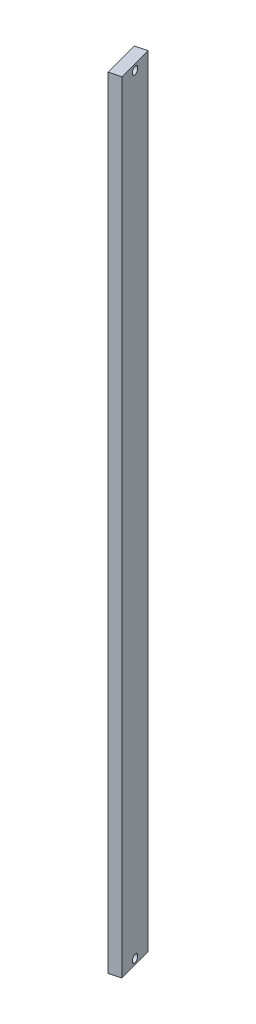
SolidWorks part; units mm, degrees
ref_plane "Front Plane" through (0, 0, 0) normal (0, 0, 1) x (1, 0, 0)
ref_plane "Top Plane" through (0, 0, 0) normal (0, 1, 0) x (1, 0, 0)
ref_plane "Right Plane" through (0, 0, 0) normal (1, 0, 0) x (0, 0, -1)
sketch "Sketch1" plane through (0, 0, 0) normal (0, 1, 0) x (1, 0, 0)
  line L0 (0, 0) -> (0, 39.444) construction
  line L1 (0, 39.444) -> (-19.722, 34.1595)
  line L2 (-19.722, 34.1595) -> (-34.1595, 19.722)
  line L3 (-34.1595, 19.722) -> (-39.444, 0)
  line L4 (-39.444, 0) -> (-34.1595, -19.722)
  line L5 (-34.1595, -19.722) -> (-19.722, -34.1595)
  line L6 (-19.722, -34.1595) -> (0, -39.444)
  line L7 (0, -39.444) -> (19.722, -34.1595)
  line L8 (19.722, -34.1595) -> (34.1595, -19.722)
  line L9 (34.1595, -19.722) -> (39.444, 0)
  line L10 (39.444, 0) -> (34.1595, 19.722)
  line L11 (34.1595, 19.722) -> (19.722, 34.1595)
  line L12 (19.722, 34.1595) -> (0, 39.444)
  line L13 (39.444, 0) -> (34.1595, 19.722)
  line L14 (39.444, 0) -> (45.5777, 1.6435)
  line L15 (34.1595, 19.722) -> (40.2932, 21.3655)
  line L16 (45.5777, 1.6435) -> (40.2932, 21.3655)
  circle A0 centre (0, 0) radius 38.1 construction
  dimension "D1" = 76.2
  dimension "D2" = 6.35
extrude "Boss-Extrude1" add sketch "Sketch1" along normal blind 431.8 contours L14 L16 L15 L10
sketch "Sketch2" plane through (36.8018, 0, -9.861) normal (-0.9659, 0, 0.2588) x (0.2588, 0, 0.9659)
  line L0 (0, 426.0719) -> (0, 411.5151) construction
  line L1 (-10.2089, 431.8) -> (-10.2089, 0) construction
  line L2 (10.2089, 431.8) -> (10.2089, 0) construction
  line L3 (0, 428.625) -> (7.9041, 428.625) construction
  line L4 (10.2089, 431.8) -> (-10.2089, 431.8) construction
  line L5 (11.9103, 425.45) -> (2.1336, 425.45) construction
  circle A0 centre (0, 428.625) radius 2.0955
  dimension "D1" = 4.191
extrude "Cut-Extrude1" cut sketch "Sketch2" against normal through all
sketch "Sketch3" plane through (36.8018, 0, -9.861) normal (-0.9659, 0, 0.2588) x (0.2588, 0, 0.9659)
  line L0 (0, 3.175) -> (0, 1.0404) construction
  line L1 (10.2089, 431.8) -> (10.2089, 0) construction
  line L2 (-10.2089, 431.8) -> (-10.2089, 0) construction
  line L3 (0, 3.175) -> (5.9584, 3.175) construction
  line L4 (10.2089, 0) -> (-10.2089, 0) construction
  line L5 (2.1336, 6.35) -> (11.9103, 6.35) construction
  circle A0 centre (0, 3.175) radius 2.0955
  circle A1 centre (0, 428.625) radius 2.0955 construction
extrude "Cut-Extrude2" cut sketch "Sketch3" against normal through all
